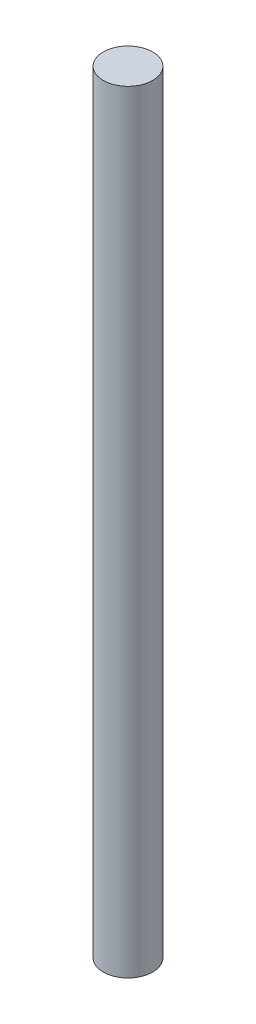
SolidWorks part; units mm, degrees
ref_plane "Front Plane" through (0, 0, 0) normal (0, 0, 1) x (1, 0, 0)
ref_plane "Top Plane" through (0, 0, 0) normal (0, 1, 0) x (1, 0, 0)
ref_plane "Right Plane" through (0, 0, 0) normal (1, 0, 0) x (0, 0, -1)
sketch "Sketch1" plane through (0, 0, 0) normal (0, 1, 0) x (1, 0, 0)
  circle A0 centre (0, 0) radius 4
  point P3 (0, 0)
extrude "Boss-Extrude1" add sketch "Sketch1" along normal blind 125
sketch "Sketch2" plane through (0, 125, 0) normal (0, 1, 0) x (1, 0, 0)
  circle A0 centre (0, 0) radius 6
